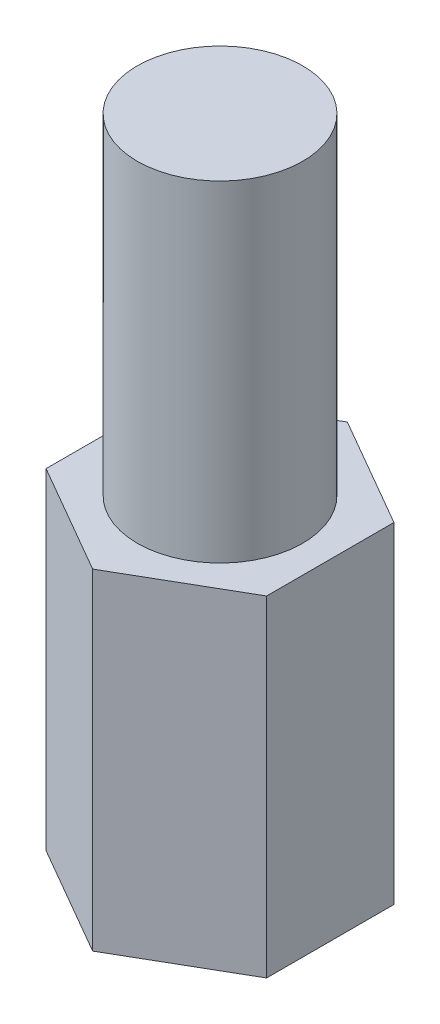
SolidWorks part; units mm, degrees
material "ABS"
ref_plane "前视基准面" through (0, 0, 0) normal (0, 0, 1) x (1, 0, 0)
ref_plane "上视基准面" through (0, 0, 0) normal (0, 1, 0) x (1, 0, 0)
ref_plane "右视基准面" through (0, 0, 0) normal (1, 0, 0) x (0, 0, -1)
sketch "草图1" plane through (0, 0, 0) normal (0, 1, 0) x (1, 0, 0)
  line L1 (0, 2.3094) -> (-2, 1.1547)
  line L2 (-2, 1.1547) -> (-2, -1.1547)
  line L3 (-2, -1.1547) -> (0, -2.3094)
  line L4 (0, -2.3094) -> (2, -1.1547)
  line L5 (2, -1.1547) -> (2, 1.1547)
  line L6 (2, 1.1547) -> (0, 2.3094)
  circle A0 centre (0, 0) radius 2 construction
  circle A1 centre (0, 0) radius 1.5
  dimension "D1" = 3
  dimension "D2" = 4
extrude "凸台-拉伸1" add sketch "草图1" along normal blind 6
sketch "草图2" plane through (0, 6, 0) normal (0, 1, 0) x (1, 0, 0)
  circle A0 centre (0, 0) radius 1.5
extrude "凸台-拉伸2" add sketch "草图2" along normal blind 6 and the other way blind 2
